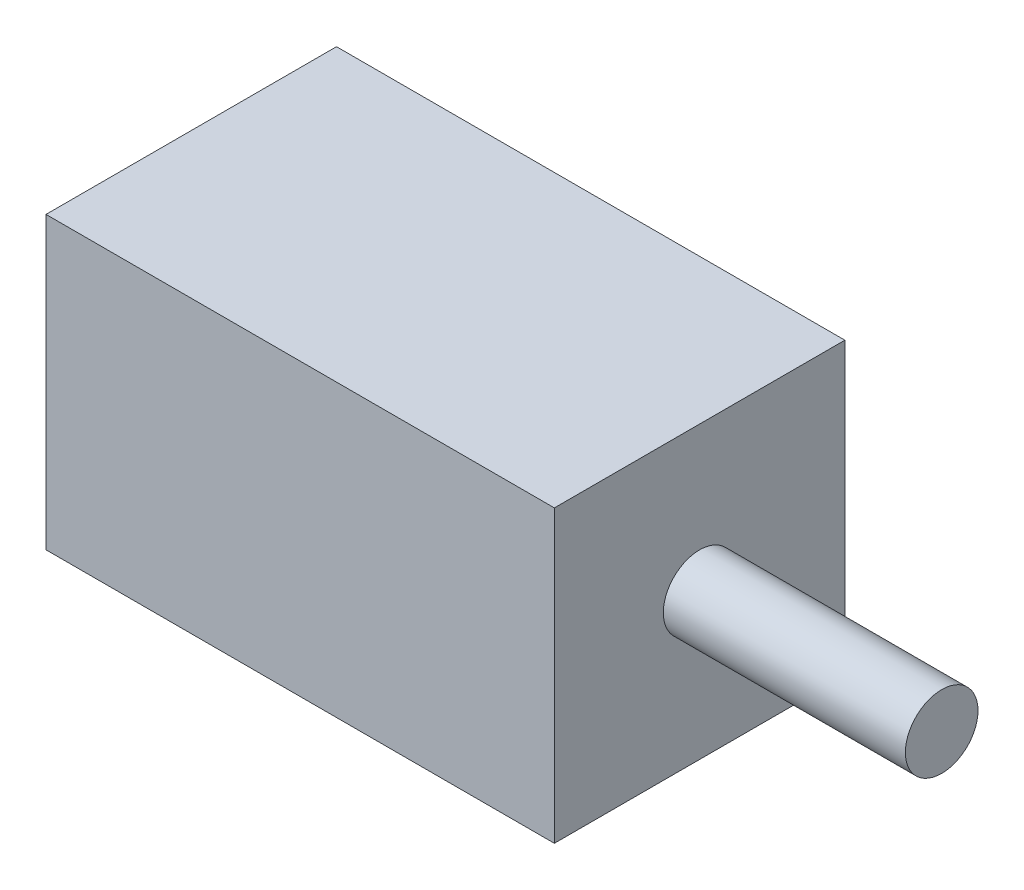
SolidWorks part; units mm, degrees
ref_plane "Front Plane" through (0, 0, 0) normal (0, 0, 1) x (1, 0, 0)
ref_plane "Top Plane" through (0, 0, 0) normal (0, 1, 0) x (1, 0, 0)
ref_plane "Right Plane" through (0, 0, 0) normal (1, 0, 0) x (0, 0, -1)
sketch "Sketch1" plane through (0, 0, 0) normal (0, 1, 0) x (1, 0, 0)
  line L1 (6.4432, 5.7869) -> (-14.5568, 5.7869)
  line L2 (6.4432, 5.7869) -> (6.4432, -6.2131)
  line L3 (6.4432, -6.2131) -> (-14.5568, -6.2131)
  line L4 (-14.5568, 5.7869) -> (-14.5568, -6.2131)
  dimension "D1" = 21
  dimension "D2" = 12
extrude "Boss-Extrude1" add sketch "Sketch1" along normal blind 12
sketch "Sketch2" plane through (6.4432, 0, 0) normal (1, 0, 0) x (0, 0, -1)
  line L0 (-6.2131, 6) -> (5.7869, 6)
  line L1 (-6.2131, 12) -> (-6.2131, 0) construction
  line L2 (5.7869, 12) -> (5.7869, 0) construction
  circle A0 centre (-0.2131, 6) radius 1.5
extrude "Boss-Extrude2" add sketch "Sketch2" along normal blind 10 contours L0 A0 | L0 A0
